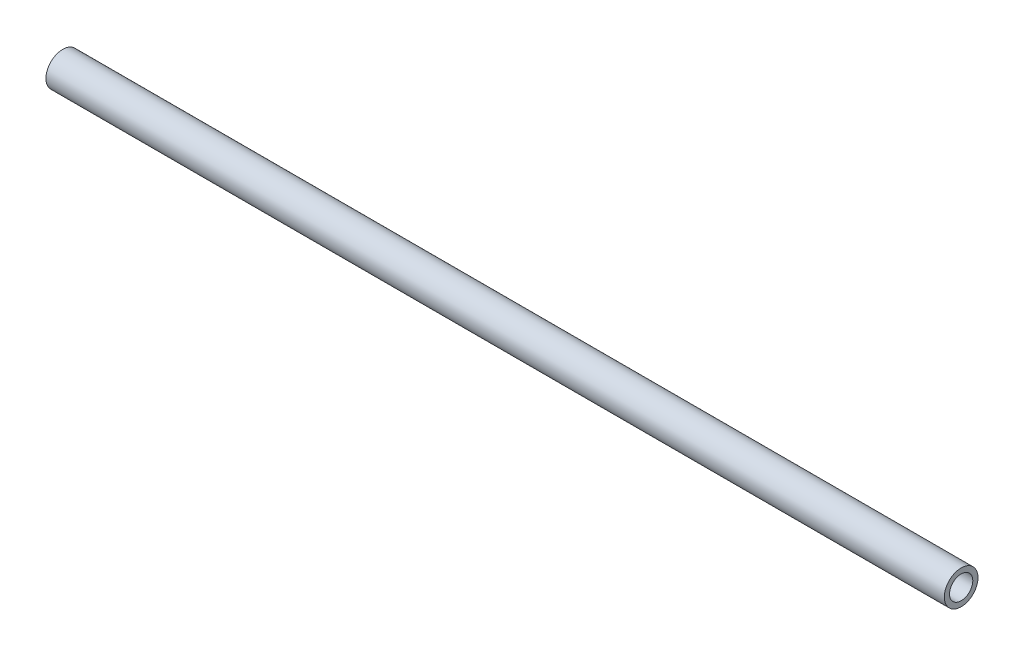
SolidWorks part; units mm, degrees
ref_plane "Front" through (0, 0, 0) normal (0, 0, 1) x (1, 0, 0)
ref_plane "Top" through (0, 0, 0) normal (0, 1, 0) x (1, 0, 0)
ref_plane "Right" through (0, 0, 0) normal (1, 0, 0) x (0, 0, -1)
sketch "Sketch1" plane through (0, 0, 0) normal (1, 0, 0) x (0, 0, -1)
  line L0 (3.2893, 0) -> (4.7625, 0) construction
  line L1 (3.2893, 0) -> (4.7625, 0) construction
  line L2 (4.0259, 0) -> (4.0259, 1.0672) construction
  circle A0 centre (0, 0) radius 4.7625
  circle A1 centre (0, 0) radius 3.2893
  point P4 (4.7625, 0)
  point P5 (3.2893, 0)
  dimension "OD" = 9.525
  dimension "ID" = 6.5786
  dimension "Wall Thickness" = 1.4732
sketch "Sketch2" plane through (0, 0, 0) normal (0, 0, 1) x (1, 0, 0)
  line L0 (-127, 0) -> (127, 0) construction
  point P2 (-115.0938, 0)
  point P3 (115.0938, 0)
  dimension "D1" = 11.9062
  dimension "D2" = 11.9062
sketch "Sketch3" plane through (0, 0, 0) normal (1, 0, 0) x (0, 0, -1)
  circle A0 centre (0, 0) radius 3.2893 construction
  circle A1 centre (0, 0) radius 4.7625 construction
  circle A2 centre (0, 0) radius 3.2893
  circle A3 centre (0, 0) radius 4.7625
extrude "Boss-Extrude1" add sketch "Sketch3" along normal mid plane 254
equation "\"D1@Boss-Extrude1\"=\"Length@Sketch2\""
equation "\"D1@Sketch2\"=\"OD@Sketch1\"*1.25"
equation "\"D2@Sketch2\"=\"D1@Sketch2\""
